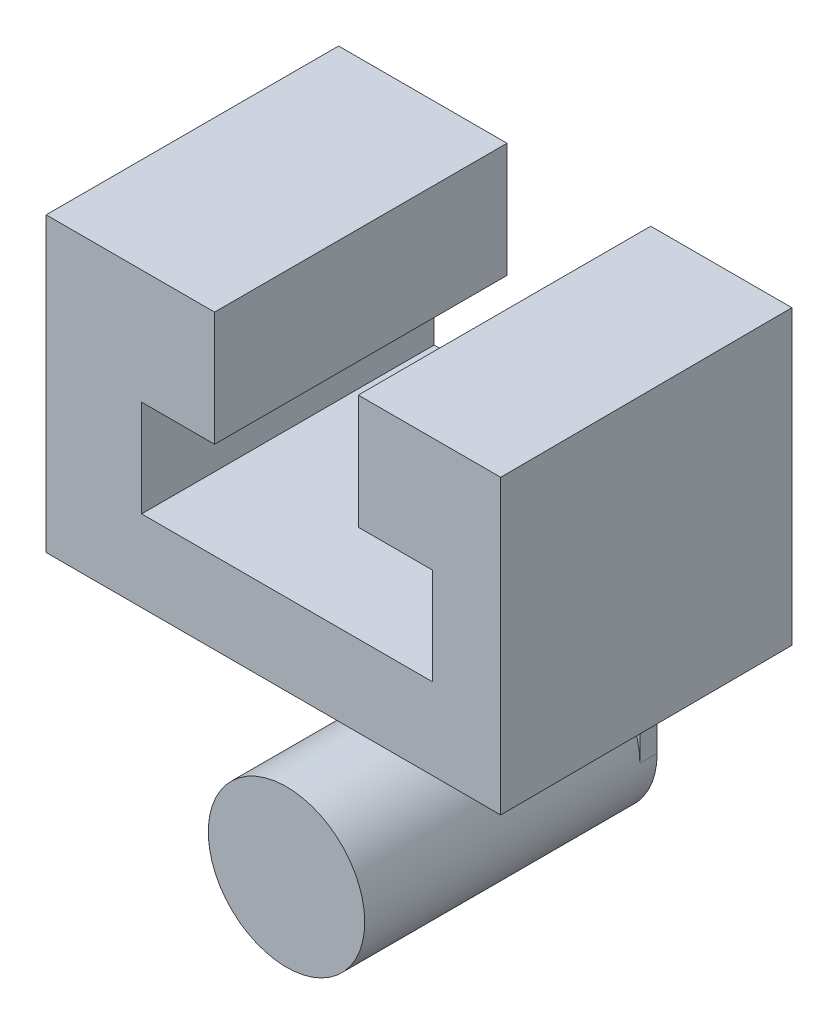
SolidWorks part; units mm, degrees
ref_plane "Front Plane" through (0, 0, 0) normal (0, 0, 1) x (1, 0, 0)
ref_plane "Top Plane" through (0, 0, 0) normal (0, 1, 0) x (1, 0, 0)
ref_plane "Right Plane" through (0, 0, 0) normal (1, 0, 0) x (0, 0, -1)
sketch "Sketch1" plane through (0, 0, 0) normal (0, 0, 1) x (1, 0, 0)
  circle A0 centre (0, 0) radius 6.7945
  dimension "D1" = 13.589
extrude "Boss-Extrude1" add sketch "Sketch1" against normal blind 25.4
sketch "Sketch2" plane through (0, 0, 0) normal (0, 1, 0) x (1, 0, 0)
  line L1 (-6.7945, 25.4) -> (6.7945, 25.4)
  line L2 (-6.7945, 25.4) -> (-6.7945, 23.8995)
  line L3 (-6.7945, 23.8995) -> (6.7945, 23.8995)
  line L4 (6.7945, 25.4) -> (6.7945, 23.8995)
extrude "Boss-Extrude2" add sketch "Sketch2" along normal blind 13.97
sketch "Sketch6" plane through (0, 13.97, 0) normal (0, 1, 0) x (1, 0, 0)
  line L1 (-20.8762, 25.4) -> (18.4938, 25.4)
  line L2 (-20.8762, 25.4) -> (-20.8762, 0)
  line L3 (-20.8762, 0) -> (18.6055, 0)
  line L4 (18.4938, 25.4) -> (18.6055, 0)
  dimension "D1" = 39.37
extrude "Boss-Extrude3" add sketch "Sketch6" along normal blind 25.4
sketch "Sketch11" plane through (0, 0, 0) normal (0, 0, 1) x (1, 0, 0)
  line L0 (0, 21.0227) -> (-12.5809, 21.0227)
  line L1 (-12.5809, 21.0227) -> (-12.5809, 29.4266)
  line L2 (-12.5809, 29.4266) -> (-6.2466, 29.4266)
  line L3 (-6.2466, 29.4266) -> (-6.2466, 39.37)
  line L4 (-6.2466, 39.37) -> (0, 39.37)
  line L5 (0, 39.37) -> (6.2337, 39.37)
  line L6 (6.2337, 39.37) -> (6.2337, 29.4266)
  line L7 (6.2337, 29.4266) -> (12.6933, 29.4266)
  line L8 (12.6933, 29.4266) -> (12.6933, 21.0227)
  line L9 (12.6933, 21.0227) -> (0, 21.0227)
extrude "Cut-Extrude1" cut sketch "Sketch11" against normal blind 27.94
equation "\"Feature A\"= ( ( 32 * 150 ) / ( pi * 10000 ) ) ^ 1 / 3"
equation "\"Feature B\" = 300 / ( 1 - \"Feature A\" ) * 10000"
equation "\"Feature C base\" = 6 * 600 / ( 1.25 ) ^ 2 * 10000"
equation "\"Feature D thickness\"= 3 + sqr ( 10809 ) / 200"
equation "\"Feature E thickness\"= sqr ( 6 * 450 / 2.5 * 10000 )"
